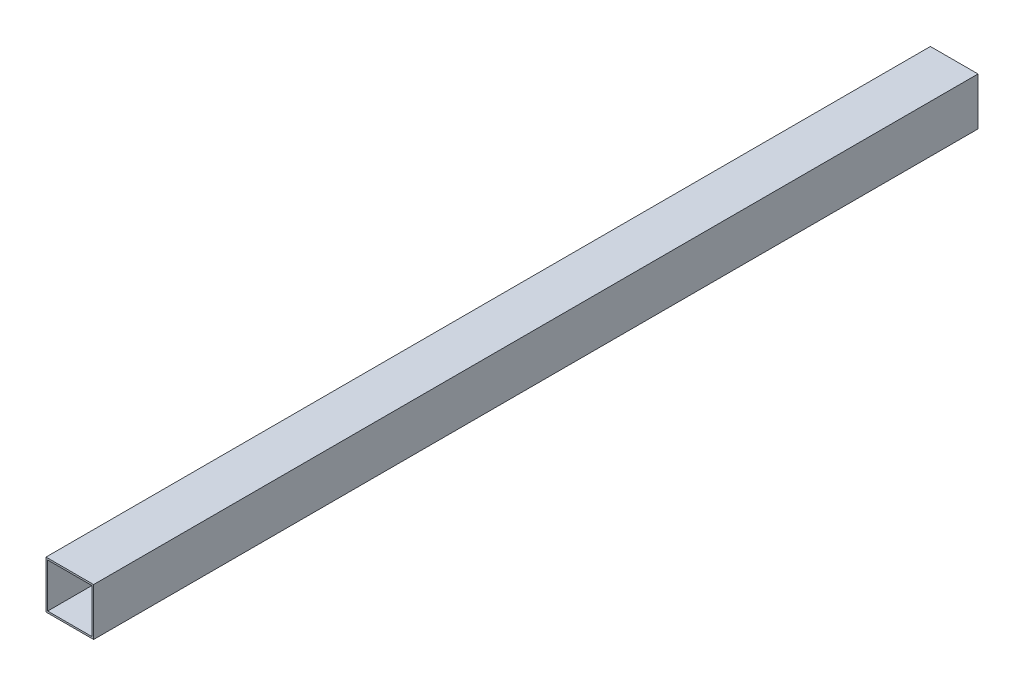
SolidWorks part; units mm, degrees
material "AISI 4340 Acero normalizado"
ref_plane "Alzado" through (0, 0, 0) normal (0, 0, 1) x (1, 0, 0)
ref_plane "Planta" through (0, 0, 0) normal (0, 1, 0) x (1, 0, 0)
ref_plane "Vista lateral" through (0, 0, 0) normal (1, 0, 0) x (0, 0, -1)
sketch "Croquis2" plane through (0, 0, 0) normal (0, 0, 1) x (1, 0, 0)
  line L0 (32.5, -32.5) -> (32.5, 32.5)
  line L1 (35, -35) -> (-35, -35)
  line L2 (35, -35) -> (35, 35)
  line L3 (35, 35) -> (-35, 35)
  line L4 (-35, -35) -> (-35, 35)
  line L5 (35, -35) -> (-35, 35) construction
  line L6 (35, 35) -> (-35, -35) construction
  line L7 (32.5, 32.5) -> (-32.5, 32.5)
  line L8 (-32.5, -32.5) -> (-32.5, 32.5)
  line L9 (32.5, -32.5) -> (-32.5, -32.5)
  point P0 (0, 0)
  dimension "D1" = 70
  dimension "D2" = 70
  dimension "D3" = 2.5
extrude "Saliente-Extruir1" add sketch "Croquis2" along normal mid plane 1300
